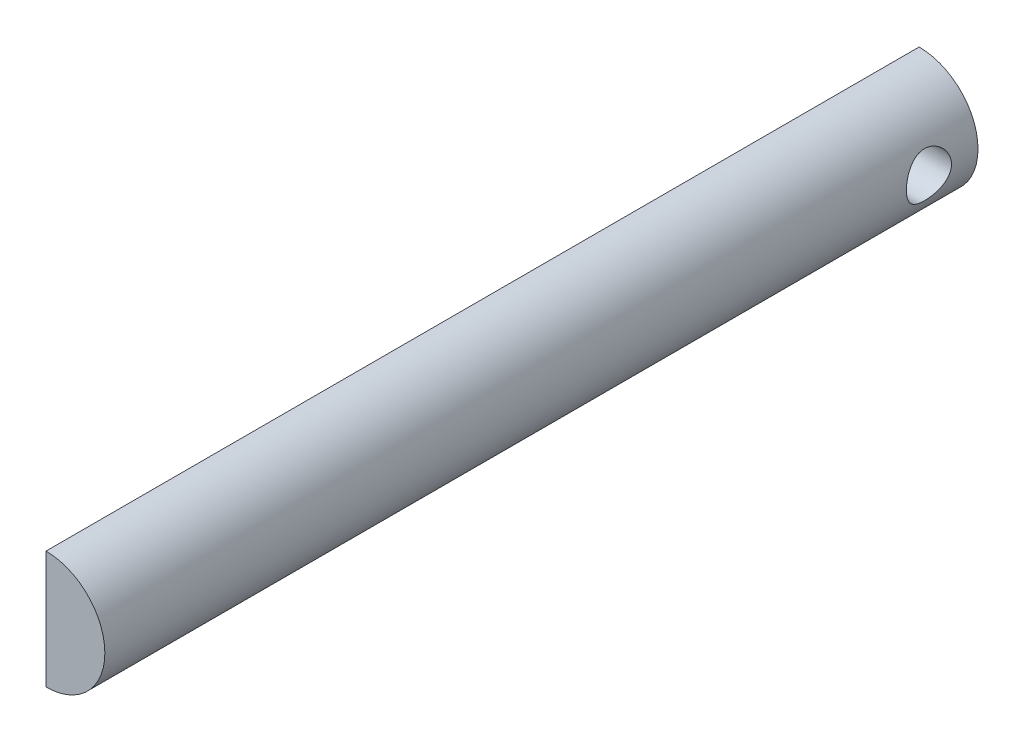
SolidWorks part; units mm, degrees
ref_plane "Plan de face" through (0, 0, 0) normal (0, 0, 1) x (1, 0, 0)
ref_plane "Plan de dessus" through (0, 0, 0) normal (0, 1, 0) x (1, 0, 0)
ref_plane "Plan de droite" through (0, 0, 0) normal (1, 0, 0) x (0, 0, -1)
sketch "Esquisse2" plane through (0, 0, 0) normal (0, 0, 1) x (1, 0, 0)
  line L0 (0, 3) -> (0, -3)
  arc A0 (0, -3) -> (0, 3) centre (0, 0) ccw
  dimension "D1" = 3
extrude "Boss.-Extru.1" add sketch "Esquisse2" along normal blind 44.5
sketch "Esquisse6" plane through (0, 0, 0) normal (-1, 0, 0) x (0, 0, 1)
  line L0 (0, 0) -> (2.5, 0) construction
  point P2 (2.5, 0)
  point P7 (2.5, 0)
  point P9 (2.5, 0)
  dimension "D1" = 2.5
hole_wizard "Diamètre du perçage Ø2.3 (2.3)2" positions "Esquisse6" profile "Esquisse4" hole size "Ø2.3" standard "ISO" end condition through all
sketch "Esquisse4" plane through (0, 0, 2.5) normal (0, 1, 0) x (0, 0, 1)
  line L0 (0, 0) -> (0, 3)
  line L1 (0, 3) -> (1.15, 3)
  line L2 (1.15, 3) -> (1.15, 0)
  line L5 (1.15, 0) -> (0, 0)
  line L11 (0, -6.35) -> (0, 107.95) construction
  dimension "Diamètre du perçage jusqu'au prochain" = 2.3
  dimension "Profondeur du perçage jusqu'au prochain" = 3
